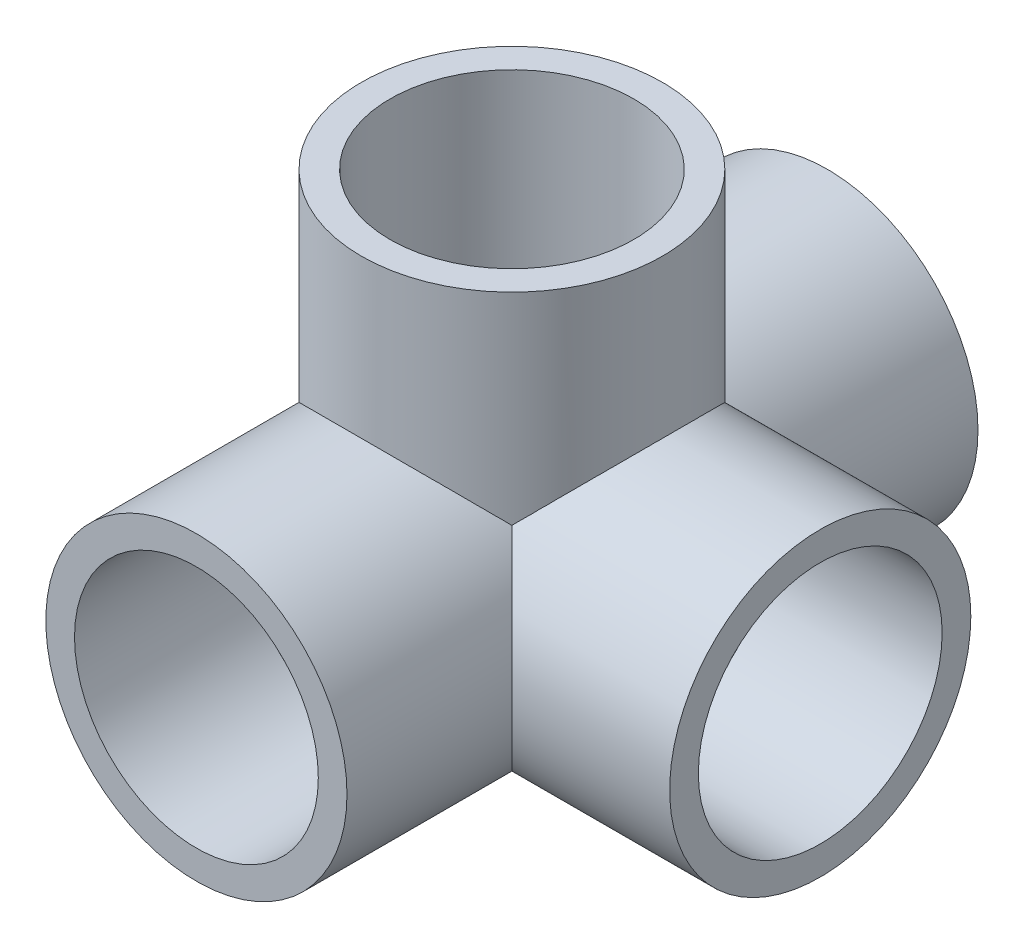
SolidWorks part; units mm, degrees
ref_plane "Front Plane" through (0, 0, 0) normal (0, 0, 1) x (1, 0, 0)
ref_plane "Top Plane" through (0, 0, 0) normal (0, 1, 0) x (1, 0, 0)
ref_plane "Right Plane" through (0, 0, 0) normal (1, 0, 0) x (0, 0, -1)
sketch "Sketch1" plane through (0, 0, 0) normal (0, 0, 1) x (1, 0, 0)
  circle A0 centre (0, 0) radius 16.6687
  dimension "D1" = 33.3375
extrude "Boss-Extrude1" add sketch "Sketch1" along normal blind 69.85
sketch "Sketch2" plane through (0, 0, 0) normal (1, 0, 0) x (0, 0, -1)
  line L0 (0, -16.6687) -> (0, 16.6687) construction
  circle A0 centre (-34.925, 0) radius 16.6687
  dimension "D1" = 34.925
  dimension "D2" = 33.3375
extrude "Boss-Extrude2" add sketch "Sketch2" along normal blind 34.1313
sketch "Sketch3" plane through (34.1313, 0, 0) normal (1, 0, 0) x (0, 0, -1)
  circle A0 centre (-34.925, 0) radius 12.7
  dimension "D1" = 25.4
extrude "Cut-Extrude1" cut sketch "Sketch3" against normal blind 30.48
sketch "Sketch5" plane through (0, 0, 0) normal (0, 0, -1) x (-1, 0, 0)
  circle A0 centre (0, 0) radius 12.7
  dimension "D1" = 25.4
extrude "Cut-Extrude3" cut sketch "Sketch5" against normal through all
sketch "Sketch7" plane through (0, 0, 69.85) normal (0, 0, 1) x (1, 0, 0)
  circle A0 centre (0, 0) radius 13.4938
  dimension "D1" = 26.9875
extrude "Cut-Extrude4" cut sketch "Sketch7" against normal blind 19.05
sketch "Sketch8" plane through (34.1313, 0, 0) normal (1, 0, 0) x (0, 0, -1)
  circle A0 centre (-34.925, 0) radius 13.4937
  dimension "D1" = 26.9875
extrude "Cut-Extrude5" cut sketch "Sketch8" against normal blind 19.05
sketch "Sketch9" plane through (0, 0, 0) normal (0, 0, -1) x (-1, 0, 0)
  circle A0 centre (0, 0) radius 13.4938
  dimension "D1" = 26.9875
extrude "Cut-Extrude6" cut sketch "Sketch9" against normal blind 19.05
sketch "Sketch10" plane through (0, 0, 0) normal (0, 1, 0) x (1, 0, 0)
  line L0 (16.6687, -51.5937) -> (0, -34.925) construction
  circle A0 centre (0, -34.925) radius 16.6687
  dimension "D1" = 33.3375
extrude "Boss-Extrude3" add sketch "Sketch10" along normal blind 34.1313 separate body
sketch "Sketch11" plane through (0, 34.1313, 0) normal (0, 1, 0) x (1, 0, 0)
  circle A0 centre (0, -34.925) radius 12.7
extrude "Cut-Extrude7" cut sketch "Sketch11" against normal blind 34.1313
sketch "Sketch12" plane through (0, 34.1313, 0) normal (0, 1, 0) x (1, 0, 0)
  circle A0 centre (0, -34.925) radius 13.4938
  dimension "D1" = 26.9875
extrude "Cut-Extrude8" cut sketch "Sketch12" against normal blind 19.05
sketch "Sketch13" plane through (0, 0, 0) normal (0, 0, -1) x (-1, 0, 0)
  circle A0 centre (0, 0) radius 12.7
extrude "Cut-Extrude9" cut sketch "Sketch13" against normal through all
sketch "Sketch14" plane through (34.1313, 0, 0) normal (1, 0, 0) x (0, 0, -1)
  circle A0 centre (-34.925, 0) radius 12.7
extrude "Cut-Extrude10" cut sketch "Sketch14" against normal blind 38.1
